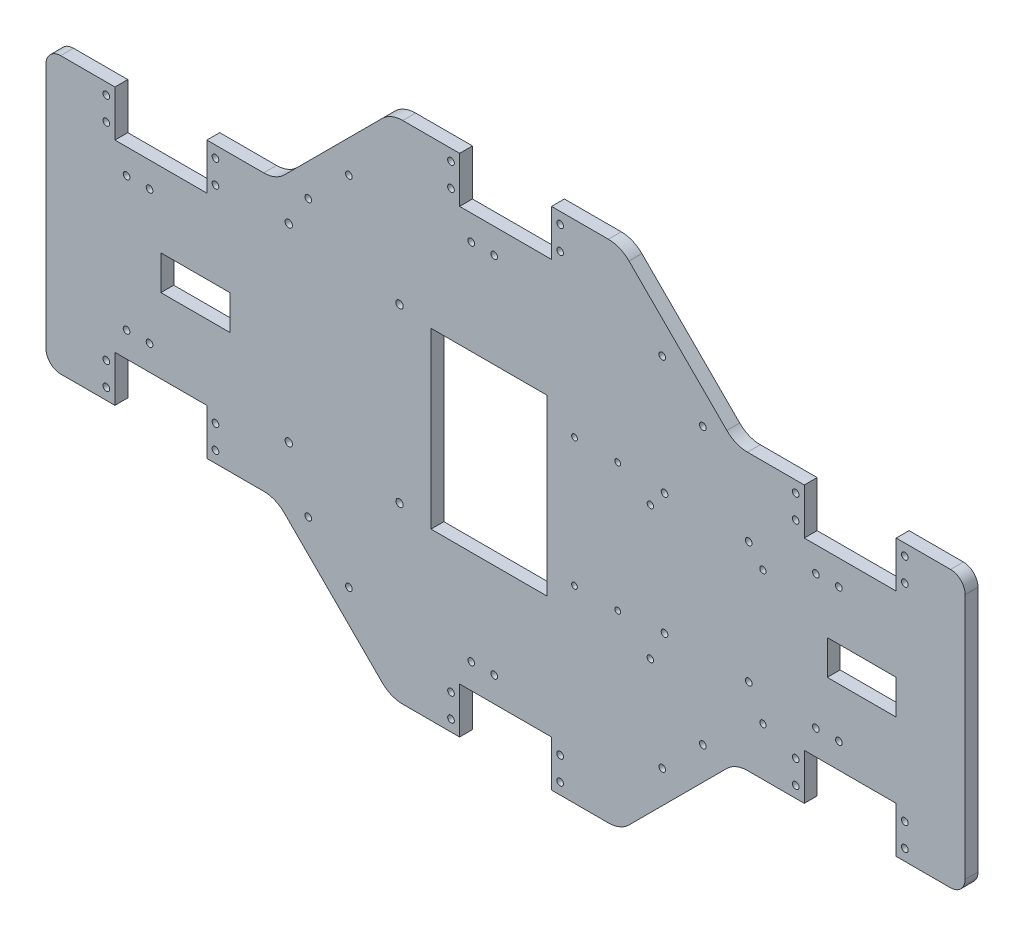
SolidWorks part; units mm, degrees
ref_plane "Front" through (0, 0, 0) normal (0, 0, 1) x (1, 0, 0)
ref_plane "Top" through (0, 0, 0) normal (0, 1, 0) x (1, 0, 0)
ref_plane "Right" through (0, 0, 0) normal (1, 0, 0) x (0, 0, -1)
sketch "Esquisse1" plane through (0, 0, 0) normal (0, 0, 1) x (1, 0, 0)
  line L0 (100, -60) -> (150, -110)
  line L1 (0, 0) -> (25.8386, 0)
  line L2 (0, 0) -> (0, -60)
  line L3 (0, -60) -> (100, -60)
  line L5 (0, 0) -> (100, -60) construction
  line L6 (0, -60) -> (25.8386, 0) construction
  line L7 (150, -110) -> (250, -110)
  line L8 (250, -110) -> (300, -60)
  line L9 (300, -60) -> (400, -60)
  line L10 (400, -60) -> (400, 0)
  line L11 (400, 0) -> (25.8386, 0)
  point P0 (0, 0)
  dimension "D1" = 100
  dimension "D2" = 100
  dimension "D3" = 100
  dimension "D4" = 135
  dimension "D5" = 135
  dimension "D6" = 0
  dimension "D7" = 50
  dimension "D8" = 60
extrude "Boss.-Extru.1" add sketch "Esquisse1" along normal blind 5.6
sketch "Esquisse2" plane through (0, 0, 5.6) normal (0, 0, 1) x (1, 0, 0)
  line L0 (0, -60) -> (100, -60) construction
  line L1 (30, -40) -> (70, -40)
  line L2 (30, -40) -> (30, -60)
  line L3 (30, -60) -> (70, -60)
  line L4 (70, -40) -> (70, -60)
  line L5 (30, -40) -> (70, -60) construction
  line L6 (30, -60) -> (70, -40) construction
  line L7 (0, 0) -> (0, -60) construction
  point P0 (0, -90)
  dimension "D1" = 20
  dimension "D2" = 40
  dimension "D3" = 30
extrude "Enlèv. mat.-Extru.1" cut sketch "Esquisse2" against normal up to next
sketch "Esquisse3" plane through (0, 0, 5.6) normal (0, 0, 1) x (1, 0, 0)
  line L0 (30, -50) -> (70, -50) construction
  line L1 (30, -40) -> (30, -60) construction
  line L2 (70, -60) -> (70, -40) construction
  circle A0 centre (26.25, -55.08) radius 1.45
  circle A1 centre (73.75, -55.08) radius 1.45
  circle A2 centre (73.75, -44.92) radius 1.45
  circle A3 centre (26.25, -44.92) radius 1.45
  circle A4 centre (35.06, -29.09) radius 1.45
  circle A5 centre (45.06, -29.09) radius 1.45
  dimension "D1" = 3.75
  dimension "D2" = 5.08
  dimension "D3" = 47.5
  dimension "D4" = 2.9
  dimension "D5" = 3.75
  dimension "D6" = 2.9
  dimension "D7" = 2.9
  dimension "D8" = 10
  dimension "D9" = 8.81
  dimension "D10" = 15.83
  dimension "D11" = 0
extrude "Enlèv. mat.-Extru.2" cut sketch "Esquisse3" against normal up to next
sketch "Sketch2" plane through (0, 0, 0) normal (0, 0, 1) x (1, 0, 0)
  line L0 (150, -110) -> (250, -110) construction
  line L1 (330, -40) -> (370, -40)
  line L2 (330, -40) -> (330, -60)
  line L3 (330, -60) -> (370, -60)
  line L4 (370, -40) -> (370, -60)
  line L5 (330, -40) -> (370, -60) construction
  line L6 (330, -60) -> (370, -40) construction
  line L7 (300, -60) -> (400, -60) construction
  line L8 (400, -60) -> (400, 0) construction
  line L9 (180, -90) -> (220, -90)
  line L10 (180, -90) -> (180, -110)
  line L11 (180, -110) -> (220, -110)
  line L12 (220, -90) -> (220, -110)
  line L13 (180, -90) -> (220, -110) construction
  line L14 (180, -110) -> (220, -90) construction
  point P0 (0, -90)
  point P11 (-35, 0)
  dimension "D1" = 20
  dimension "D2" = 40
  dimension "D3" = 30
  dimension "D4" = 40
  dimension "D5" = 20
  dimension "D6" = 30
extrude "Cut-Extrude2" cut sketch "Sketch2" against normal through all and the other way through all
sketch "Sketch5" plane through (0, 0, 0) normal (0, 0, 1) x (1, 0, 0)
  line L0 (180, -100) -> (220, -100) construction
  line L1 (220, -110) -> (220, -90) construction
  line L2 (330, -50) -> (370, -50) construction
  line L4 (370, -60) -> (370, -40) construction
  line L5 (330, -40) -> (330, -60) construction
  circle A0 centre (176.25, -105.08) radius 1.45
  circle A1 centre (223.75, -105.08) radius 1.45
  circle A2 centre (223.75, -94.92) radius 1.45
  circle A3 centre (176.25, -94.92) radius 1.45
  circle A4 centre (326.25, -55.08) radius 1.45
  circle A5 centre (373.75, -55.08) radius 1.45
  circle A6 centre (373.75, -44.92) radius 1.45
  circle A7 centre (326.25, -44.92) radius 1.45
  circle A8 centre (185.06, -79.09) radius 1.45
  circle A9 centre (195.06, -79.09) radius 1.45
  circle A10 centre (335.06, -29.09) radius 1.45
  circle A11 centre (345.06, -29.09) radius 1.45
  dimension "D1" = 5.08
  dimension "D2" = 5.08
  dimension "D3" = 47.5
  dimension "D4" = 2.9
  dimension "D5" = 3.75
  dimension "D10" = 2.9
  dimension "D11" = 2.9
  dimension "D12" = 2.9
  dimension "D16" = 2.9
  dimension "D17" = 2.9
  dimension "D6" = 5.08
  dimension "D7" = 5.08
  dimension "D8" = 3.75
  dimension "D9" = 3.75
  dimension "D13" = 10
  dimension "D14" = 8.81
  dimension "D15" = 15.83
  dimension "D18" = 8.81
  dimension "D19" = 15.83
  dimension "D20" = 10
  dimension "D21" = 0
  dimension "D22" = 0
extrude "Cut-Extrude4" cut sketch "Sketch5" along normal through all
mirror "Mirror1" about plane through (0, 0, 0) normal (0, 1, 0) of "Cut-Extrude4", "Cut-Extrude2", "Enlèv. mat.-Extru.1", "Enlèv. mat.-Extru.2", "Boss.-Extru.1"
sketch "Esquisse4" plane through (0, 0, 5.6) normal (0, 0, 1) x (1, 0, 0)
  circle A0 centre (263, -39) radius 1.375
  circle A4 centre (312, -39) radius 1.375
  circle A5 centre (312, 19) radius 1.375
  circle A6 centre (263, 19) radius 1.375
  dimension "D1" = 2.75
  dimension "D2" = 2
  dimension "D3" = 43
  dimension "D4" = 51
  dimension "D5" = 2
extrude "Enlèv. mat.-Extru.4" cut sketch "Esquisse4" against normal through all
sketch "Esquisse6" plane through (0, 0, 0) normal (0, 0, -1) x (-1, 0, 0)
  circle A0 centre (-269.19, -26.31) radius 1.45
  circle A4 centre (-305.82, -26.31) radius 1.45
  circle A5 centre (-305.82, 26.52) radius 1.45
  circle A6 centre (-269.19, 26.52) radius 1.45
  dimension "D1" = 2.9
  dimension "D2" = 2
  dimension "D3" = 63.69
  dimension "D4" = 49.19
  dimension "D5" = 2
extrude "Enlèv. mat.-Extru.6" cut sketch "Esquisse6" against normal through all
sketch "Esquisse8" plane through (0, 0, 0) normal (0, 0, -1) x (-1, 0, 0)
  circle A0 centre (-230, 27.95) radius 1.25
  circle A1 centre (-248.8, 27.95) radius 1.25
  circle A2 centre (-248.8, -27.95) radius 1.25
  circle A3 centre (-230, -27.95) radius 1.25
  dimension "D1" = 2.5
  dimension "D2" = 70
  dimension "D3" = 32.05
  dimension "D4" = 2
  dimension "D5" = 2
extrude "Enlèv. mat.-Extru.7" cut sketch "Esquisse8" against normal through all
sketch "Esquisse9" plane through (0, 0, 0) normal (0, 0, -1) x (-1, 0, 0)
  circle A1 centre (-153.859, -34.88) radius 1.6
  circle A2 centre (-105.639, -36.11) radius 1.6
  circle A3 centre (-105.639, 46.36) radius 1.6
  circle A4 centre (-153.859, 40) radius 1.6
  dimension "D8" = 1.23
  dimension "D1" = 74.88
  dimension "D2" = 82.47
  dimension "D3" = 48.22
  dimension "D4" = 48.22
  dimension "D5" = 48.22
  dimension "D6" = 26.141
  dimension "D7" = 50
extrude "Enlèv. mat.-Extru.8" cut sketch "Esquisse9" against normal through all
sketch "Esquisse10" plane through (0, 0, 0) normal (0, 0, -1) x (-1, 0, 0)
  line L0 (-218, -37.85) -> (-218, 37.84)
  line L1 (-218, 37.84) -> (-167.55, 37.84)
  line L2 (-167.55, 37.84) -> (-167.55, -37.85)
  line L3 (-167.55, -37.85) -> (-218, -37.85)
  dimension "D1" = 50.45
  dimension "D2" = 75.69
  dimension "D3" = 2
  dimension "D4" = 52.16
extrude "Enlèv. mat.-Extru.9" cut sketch "Esquisse10" against normal through all
sketch "Esquisse11" plane through (0, 0, 0) normal (0, 0, -1) x (-1, 0, 0)
  line L1 (-340, 7.5) -> (-370, 7.5)
  line L2 (-340, 7.5) -> (-340, -7.5)
  line L3 (-340, -7.5) -> (-370, -7.5)
  line L4 (-370, 7.5) -> (-370, -7.5)
  line L5 (-50, 7.5) -> (-80, 7.5)
  line L6 (-50, 7.5) -> (-50, -7.5)
  line L7 (-50, -7.5) -> (-80, -7.5)
  line L8 (-80, 7.5) -> (-80, -7.5)
  dimension "D1" = 30
  dimension "D2" = 30
  dimension "D3" = 30
  dimension "D4" = 50
  dimension "D5" = 15
  dimension "D6" = 15
  dimension "D7" = 52.5
  dimension "D8" = 52.5
extrude "Enlèv. mat.-Extru.10" cut sketch "Esquisse11" against normal through all
ref_plane "Plan1" through (200, 0, 0) normal (-1, 0, 0) x (0, 0, 1)
ref_plane "Plan2" through (0, 0, 0) normal (0, 1, 0) x (1, 0, 0)
sketch "Esquisse12" plane through (0, 0, 5.6) normal (0, 0, 1) x (1, 0, 0)
  line L1 (200, 24.0954) -> (200, -24.0954) construction
  line L2 (22.5792, 0) -> (-22.5792, 0) construction
  line L3 (100, 60) -> (150, 110) construction
  circle A0 centre (131.8198, 77.6777) radius 1.45
  circle A1 centre (114.1421, 60) radius 1.45
  circle A2 centre (285.8579, 60) radius 1.45
  circle A3 centre (268.1802, 77.6777) radius 1.45
  circle A4 centre (285.8579, -60) radius 1.45
  circle A5 centre (268.1802, -77.6777) radius 1.45
  circle A6 centre (131.8198, -77.6777) radius 1.45
  circle A7 centre (114.1421, -60) radius 1.45
  dimension "D1" = 2.9
  dimension "D2" = 2.9
  dimension "D3" = 25
  dimension "D4" = 10
  dimension "D5" = 14.1421
  dimension "D6" = 0
extrude "Enlèv. mat.-Extru.11" cut sketch "Esquisse12" against normal through all
fillet "Fillet1" radius 6.35 4 edges at (400, 60, 2.8) (400, -60, 2.8) (0, -60, 2.8) (0, 60, 2.8)
fillet "Fillet2" radius 12.7 8 edges at (150, -110, 2.8) (100, -60, 2.8) (250, -110, 2.8) (300, -60, 2.8) (300, 60, 2.8) (250, 110, 2.8) (150, 110, 2.8) (100, 60, 2.8)
